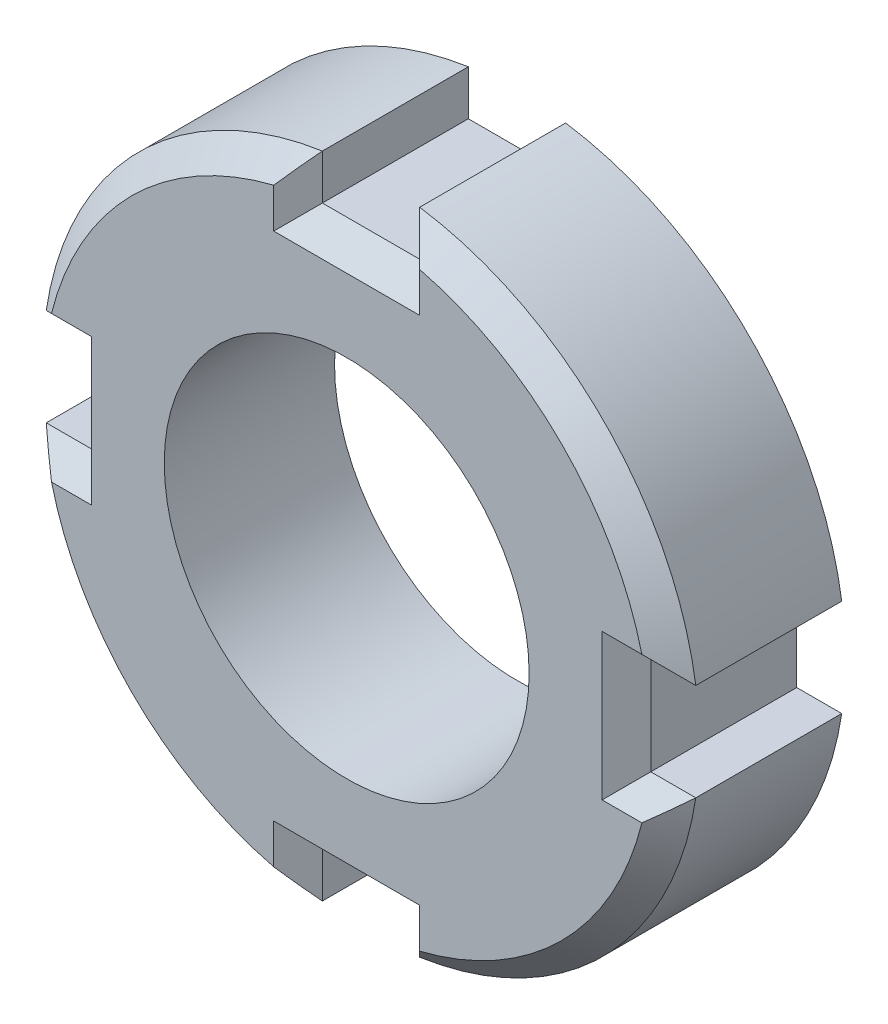
SolidWorks part; units mm, degrees
ref_plane "Front Plane" through (0, 0, 0) normal (0, 0, 1) x (1, 0, 0)
ref_plane "Top Plane" through (0, 0, 0) normal (0, 1, 0) x (1, 0, 0)
ref_plane "Right Plane" through (0, 0, 0) normal (1, 0, 0) x (0, 0, -1)
sketch "Sketch1" plane through (0, 0, 0) normal (0, 0, 1) x (1, 0, 0)
  line L0 (0, 0) -> (0, 15.6114) construction
  line L1 (0, 13.5) -> (-21.2727, 13.5) construction
  line L2 (11.5, 2) -> (15.5, 2)
  line L3 (-2, 11.5) -> (2, 11.5)
  line L4 (-2, 11.5) -> (-2, 15.5)
  line L5 (-2, 15.5) -> (2, 15.5)
  line L6 (2, 11.5) -> (2, 15.5)
  line L7 (-2, 11.5) -> (2, 15.5) construction
  line L8 (-2, 15.5) -> (2, 11.5) construction
  line L9 (11.5, 2) -> (11.5, -2)
  line L10 (11.5, -2) -> (15.5, -2)
  line L11 (15.5, 2) -> (15.5, -2)
  line L12 (2, -11.5) -> (2, -15.5)
  line L13 (2, -11.5) -> (-2, -11.5)
  line L14 (-2, -11.5) -> (-2, -15.5)
  line L15 (2, -15.5) -> (-2, -15.5)
  line L16 (-11.5, -2) -> (-15.5, -2)
  line L17 (-11.5, -2) -> (-11.5, 2)
  line L18 (-11.5, 2) -> (-15.5, 2)
  line L19 (-15.5, -2) -> (-15.5, 2)
  circle A0 centre (0, 0) radius 13.5
  circle A1 centre (0, 0) radius 7.5
  circle A2 centre (0, 0) radius 18.2906 construction
  circle A3 centre (0, 0) radius 18.2906 construction
  circle A4 centre (0, 0) radius 18.2906 construction
  circle A5 centre (0, 0) radius 18.2906 construction
  point P30 (0, 0)
  dimension "D1" = 27
  dimension "D2" = 15
  dimension "D3" = 4
  dimension "D4" = 2
  dimension "D5" = 4
extrude "Boss-Extrude1" add sketch "Sketch1" along normal blind 7 contours L2 A0 L6 L3 L4 L18 L17 L16 L14 L13 L12 L10 L9 A1
chamfer "Chamfer1" distance 1 angle 45 16 edges at (11.5, 0, 7) (12.4255, -2, 7) (9.5459, -9.5459, 7) (2, -12.4255, 7) (0, -11.5, 7) (-2, -12.4255, 7) (-9.5459, -9.5459, 7) (-12.4255, -2, 7) (-11.5, 0, 7) (-12.4255, 2, 7) (-9.5459, 9.5459, 7) (-2, 12.4255, 7) (0, 11.5, 7) (2, 12.4255, 7) (9.5459, 9.5459, 7) (12.4255, 2, 7)
